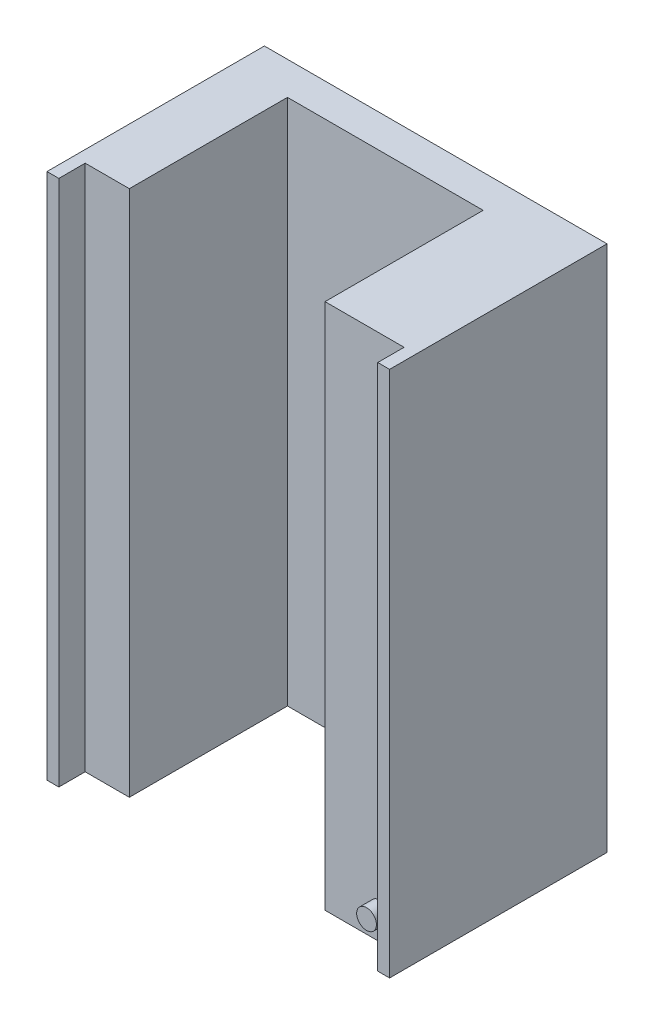
SolidWorks part; units mm, degrees
ref_plane "Top" through (0, 0, 0) normal (0, 0, 1) x (1, 0, 0)
ref_plane "Front" through (0, 0, 0) normal (0, 1, 0) x (1, 0, 0)
ref_plane "Right" through (0, 0, 0) normal (1, 0, 0) x (0, 0, -1)
sketch "Profile Sketch" plane through (0.0456, 0, -0.0242) normal (0, 1, 0) x (-1, 0, 0)
  line L0 (5.9456, -11.9758) -> (5.9456, 0.0242)
  line L1 (5.9456, 0.0242) -> (-0.0544, 0.0242)
  line L2 (-0.9544, 2.0242) -> (-0.9544, -14.4758)
  line L3 (-0.9544, -14.4758) -> (25.0456, -14.4758)
  line L4 (5.9456, -11.9758) -> (20.7956, -11.9758)
  line L5 (25.0456, -14.4758) -> (25.0456, 2.0242)
  line L6 (24.1456, 0.0242) -> (20.7956, 0.0242)
  line L7 (20.7956, 0.0242) -> (20.7956, -11.9758)
  line L8 (-0.0544, 0.0242) -> (-0.0544, 2.0242)
  line L9 (-0.9544, 2.0242) -> (-0.0544, 2.0242)
  line L10 (24.1456, 0.0242) -> (24.1456, 2.0242)
  line L11 (24.1456, 2.0242) -> (25.0456, 2.0242)
  line L12 (24.0456, 0.0242) -> (24.0456, 2.0242) construction
  dimension "D2" = 6
  dimension "Pocket Width" = 14.85
  dimension "Wall Height" = 2
  dimension "Tape Depth" = 12
  dimension "D8" = 0.1
  dimension "Reel Width" = 24
  dimension "D4" = 0.1
  dimension "Wall Thickness" = 1
  dimension "D1" = 14.5
extrude "Profile Extrude" add sketch "Profile Sketch" along normal blind 40
sketch "Sprocket Sketch" plane through (0, 0, 0) normal (0, 0, 1) x (1, 0, 0)
  circle A0 centre (-1.75, 2) radius 0.75
  dimension "D2" = 1.5
  dimension "D1" = 1.85
  dimension "D3" = 2
extrude "Sprocket Extrude" add sketch "Sprocket Sketch" along normal blind 1 contours A0
equation "\"Tape Clearance\"= 0.1mm"
equation "\"D1@Sprocket Sketch\" = \"Tape Clearance\" + 1.75"
equation "\"tap\"=0.427139"
equation "\"D8@Profile Sketch\"=\"Tape Clearance\""
equation "\"D4@Profile Sketch\"=\"Tape Clearance\""
